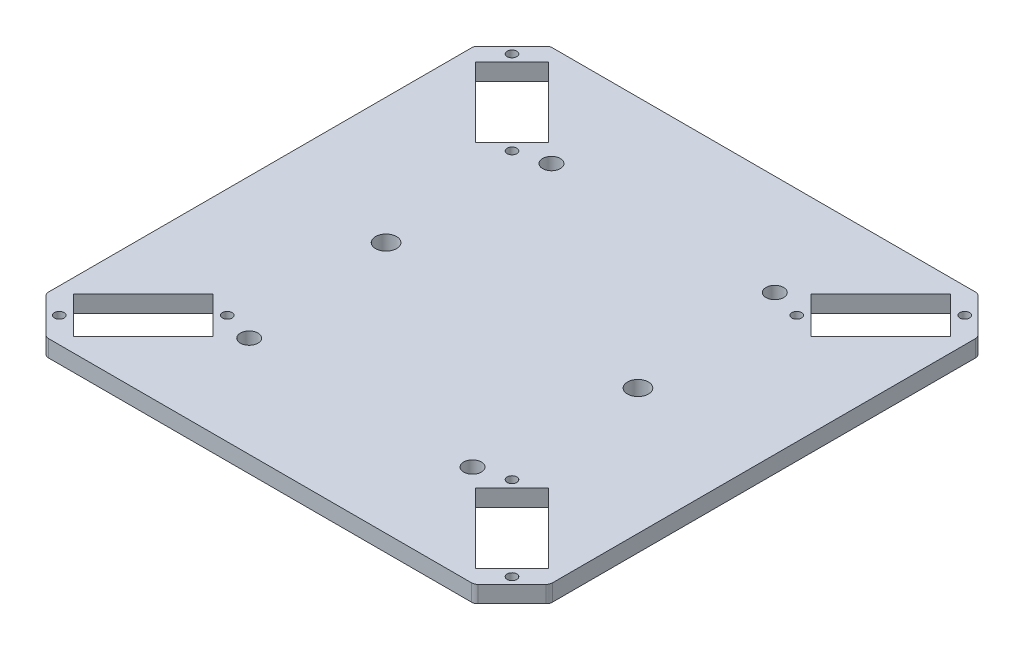
SolidWorks part; units mm, degrees
ref_plane "Front Plane" through (0, 0, 0) normal (0, 0, 1) x (1, 0, 0)
ref_plane "Top Plane" through (0, 0, 0) normal (0, 1, 0) x (1, 0, 0)
ref_plane "Right Plane" through (0, 0, 0) normal (1, 0, 0) x (0, 0, -1)
sketch "Sketch1" plane through (0, 0, 0) normal (0, 1, 0) x (1, 0, 0)
  line L31 (-56.5705, 47.8731) -> (-47.8731, 56.5705)
  line L36 (-60, 51) -> (-60, -51)
  line L38 (60, 51) -> (60, -51)
  line L39 (-60, 60) -> (60, -60) construction
  line L40 (-60, -60) -> (60, 60) construction
  line L41 (-56.5705, 47.8731) -> (-39.9535, 31.2561)
  line L42 (-47.8731, 56.5705) -> (-31.2561, 39.9535)
  line L43 (-39.9535, 31.2561) -> (-31.2561, 39.9535)
  line L44 (-60, 51) -> (-51, 60)
  line L49 (-51, 60) -> (51, 60)
  line L54 (-51, -60) -> (51, -60)
  line L55 (51, 60) -> (60, 51)
  line L56 (51, -60) -> (60, -51)
  line L57 (-60, -51) -> (-51, -60)
  line L58 (0, -1000) -> (0, 49000) construction
  line L59 (-1000.2392, 0) -> (-32.5, 0) construction
  line L60 (39.9535, 31.2561) -> (31.2561, 39.9535)
  line L61 (56.5705, 47.8731) -> (39.9535, 31.2561)
  line L62 (47.8731, 56.5705) -> (31.2561, 39.9535)
  line L63 (56.5705, 47.8731) -> (47.8731, 56.5705)
  line L64 (-47.8731, -56.5705) -> (-56.5705, -47.8731)
  line L65 (-56.5705, -47.8731) -> (-39.9535, -31.2561)
  line L66 (-47.8731, -56.5705) -> (-31.2561, -39.9535)
  line L67 (-31.2561, -39.9535) -> (-39.9535, -31.2561)
  line L68 (47.8731, -56.5705) -> (56.5705, -47.8731)
  line L69 (47.8731, -56.5705) -> (31.2561, -39.9535)
  line L70 (56.5705, -47.8731) -> (39.9535, -31.2561)
  line L71 (31.2561, -39.9535) -> (39.9535, -31.2561)
  line L75 (-32.5, 0) -> (32.5, 0) construction
  line L76 (32.5, 0) -> (48999.7608, 0) construction
  circle A0 centre (-53.9189, 53.9189) radius 1.15
  circle A1 centre (-33.9078, 33.9078) radius 1.15
  circle A2 centre (33.9078, 33.9078) radius 1.15
  circle A3 centre (53.9189, 53.9189) radius 1.15
  circle A4 centre (-53.9189, -53.9189) radius 1.15
  circle A5 centre (-33.9078, -33.9078) radius 1.15
  circle A6 centre (53.9189, -53.9189) radius 1.15
  circle A7 centre (33.9078, -33.9078) radius 1.15
  circle A12 centre (-30, 0) radius 2.5
  circle A13 centre (30, 0) radius 2.5
  circle A15 centre (26.5992, 36) radius 2.1 construction
  circle A16 centre (26.5992, 36) radius 2.1
  circle A17 centre (26.5992, -36) radius 2.1 construction
  circle A18 centre (-26.5992, -36) radius 2.1 construction
  circle A19 centre (26.5992, -36) radius 2.1
  circle A20 centre (-26.5992, -36) radius 2.1
  circle A21 centre (-26.5992, 36) radius 2.1 construction
  circle A22 centre (-26.5992, 36) radius 2.1
  point P0 (0, 0)
  point P5 (-35.6048, 35.6048)
  dimension "D5" = 2.3
  dimension "D6" = 2.4
  dimension "D7" = 11
  dimension "D8" = 2.3
  dimension "D17" = 5
  dimension "D18" = 30
  dimension "D1" = 120
  dimension "D2" = 120
  dimension "D3" = 23.5
  dimension "D4" = 12.3
  dimension "D9" = 2.4
  dimension "D19" = 30
extrude "Boss-Extrude1" add sketch "Sketch1" along normal blind 4
fillet "Fillet1" radius 1.5 8 edges at (-51, 2, -60) (-60, 2, -51) (-60, 2, 51) (-51, 2, 60) (51, 2, 60) (60, 2, 51) (51, 2, -60) (60, 2, -51)
sketch "Sketch2" plane through (0, 0, 0) normal (0, -1, 0) x (1, 0, 0)
  line L6 (-22, 40) -> (22, 40)
  line L11 (-22, 40) -> (-22, -40)
  line L13 (-22, -40) -> (22, -40)
  line L14 (22, 40) -> (22, -40)
  line L15 (-22, 40) -> (22, -40) construction
  line L20 (-22, -40) -> (22, 40) construction
  point P0 (0, 0)
  dimension "D1" = 44
  dimension "D2" = 80
